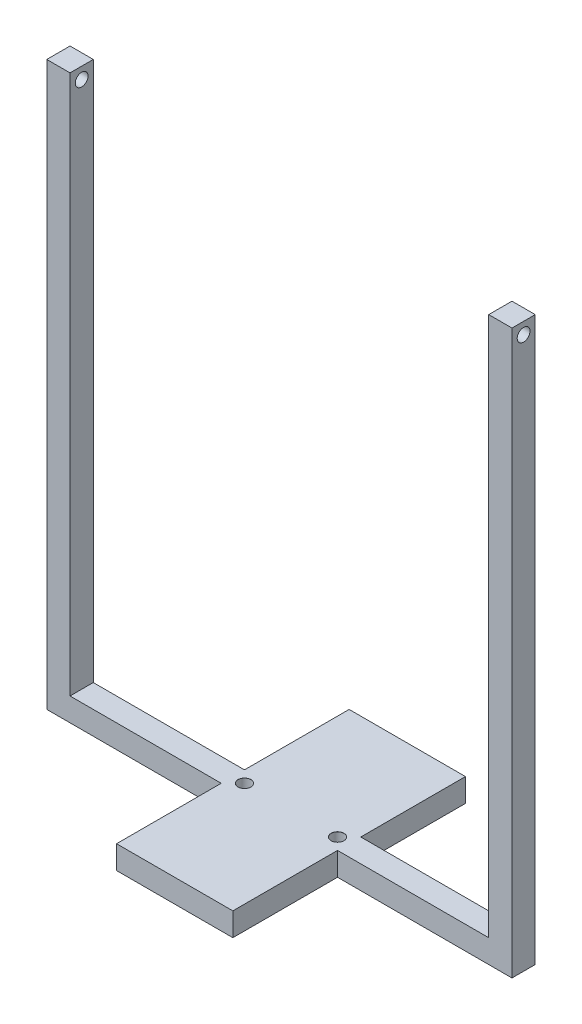
SolidWorks part; units mm, degrees
ref_plane "Front Plane" through (0, 0, 0) normal (0, 0, 1) x (1, 0, 0)
ref_plane "Top Plane" through (0, 0, 0) normal (0, 1, 0) x (1, 0, 0)
ref_plane "Right Plane" through (0, 0, 0) normal (1, 0, 0) x (0, 0, -1)
sketch "Sketch1" plane through (0, 0, 0) normal (0, 1, 0) x (1, 0, 0)
  circle A0 centre (0, 0) radius 10
  dimension "D1" = 20
extrude "Boss-Extrude1" add sketch "Sketch1" along normal blind 10
sketch "Sketch4" plane through (0, 10, 0) normal (0, 1, 0) x (1, 0, 0)
  circle A0 centre (0, 0) radius 15
  dimension "D1" = 30
extrude "Boss-Extrude4" add sketch "Sketch4" along normal blind 5
sketch "Sketch2" plane through (0, 15, 0) normal (0, 1, 0) x (1, 0, 0)
  line L0 (-25, 5) -> (-25, 50)
  line L1 (-100, 5) -> (100, 5)
  line L2 (-100, 5) -> (-100, -5)
  line L3 (-100, -5) -> (100, -5)
  line L4 (100, 5) -> (100, -5)
  line L5 (-100, 5) -> (100, -5) construction
  line L6 (-100, -5) -> (100, 5) construction
  line L7 (-25, 50) -> (25, 50)
  line L8 (25, 50) -> (25, 5)
  line L9 (25, 5) -> (-25, 5)
  line L10 (-25, -5) -> (-25, -50)
  line L11 (-25, -50) -> (25, -50)
  line L12 (25, -50) -> (25, -5)
  line L13 (25, -5) -> (-25, -5)
  point P0 (0, 0)
  point P12 (0, 50)
  circle M6 centre (0, 0) radius 15
  dimension "D1" = 10
  dimension "D2" = 200
  dimension "D3" = 100
  dimension "D4" = 50
extrude "Boss-Extrude2" add sketch "Sketch2" along normal blind 10 contours L8 L7 L0 L1 M6 | L2 L3 L1 M6 | L11 L12 L3 L10 M6 | L4 L1 L3 M6 | L3 L1 M6 | L1 M6 | L3 M6
sketch "Sketch3" plane through (0, 25, 0) normal (0, 1, 0) x (1, 0, 0)
  line L1 (-100, 5) -> (-90, 5)
  line L2 (-100, 5) -> (-100, -5)
  line L3 (-100, -5) -> (-90, -5)
  line L4 (-90, 5) -> (-90, -5)
  line L5 (-100, -5) -> (-25, -5) construction
  line L6 (100, 5) -> (90, 5)
  line L7 (100, 5) -> (100, -5)
  line L8 (100, -5) -> (90, -5)
  line L9 (90, 5) -> (90, -5)
  line L10 (25, -5) -> (100, -5) construction
  point P5 (-100, 5)
  point P6 (-90, -5)
  point P15 (100, 5)
  point P17 (90, -5)
  dimension "D1" = 10
extrude "Boss-Extrude3" add sketch "Sketch3" along normal blind 232
sketch "Sketch7" plane through (-100, 0, 0) normal (-1, 0, 0) x (0, 0, 1)
  line L0 (-5, 257) -> (5, 257) construction
  point P0 (0, 252)
  point P5 (0, 257)
  dimension "D1" = 5
hole_wizard "M5 Clearance Hole1" positions "Sketch7" profile "Sketch6" hole size "M5" standard "ANSI Metric" end condition through all
sketch "Sketch6" plane through (-100, 252, 0) normal (0, 1, 0) x (0, 0, 1)
  line L0 (0, 0) -> (0, 200)
  line L1 (0, 200) -> (2.75, 200)
  line L2 (2.75, 200) -> (2.75, 0.025)
  line L3 (2.75, 0.025) -> (2.775, 0)
  line L5 (2.775, 0) -> (0, 0)
  line L6 (-2.75, 0.025) -> (-2.775, 0) construction
  line L11 (0, -6.35) -> (0, 107.95) construction
  dimension "Thru Hole Dia." = 5.5
  dimension "Thru Hole Depth" = 200
  dimension "Near C'Sink Dia." = 5.55
  dimension "Near C'Sink Angle" = 90
sketch "Sketch11" plane through (0, 25, 0) normal (0, 1, 0) x (1, 0, 0)
  line L0 (-20, 0) -> (20, 0) construction
  point P0 (-20, 0)
  point P2 (20, 0)
  point P8 (0, 0)
  point P10 (-15.2286, 12.9649)
  dimension "D1" = 40
hole_wizard "M5 Clearance Hole2" positions "Sketch11" profile "Sketch10" hole size "M5" standard "ANSI Metric" end condition through all
sketch "Sketch10" plane through (-20, 25, 0) normal (1, 0, 0) x (0, 0, 1)
  line L0 (0, 0) -> (0, 25)
  line L1 (0, 25) -> (2.75, 25)
  line L2 (2.75, 25) -> (2.75, 0.025)
  line L3 (2.75, 0.025) -> (2.775, 0)
  line L5 (2.775, 0) -> (0, 0)
  line L6 (-2.75, 0.025) -> (-2.775, 0) construction
  line L11 (0, -6.35) -> (0, 107.95) construction
  dimension "Thru Hole Dia." = 5.5
  dimension "Thru Hole Depth" = 25
  dimension "Near C'Sink Dia." = 5.55
  dimension "Near C'Sink Angle" = 90
